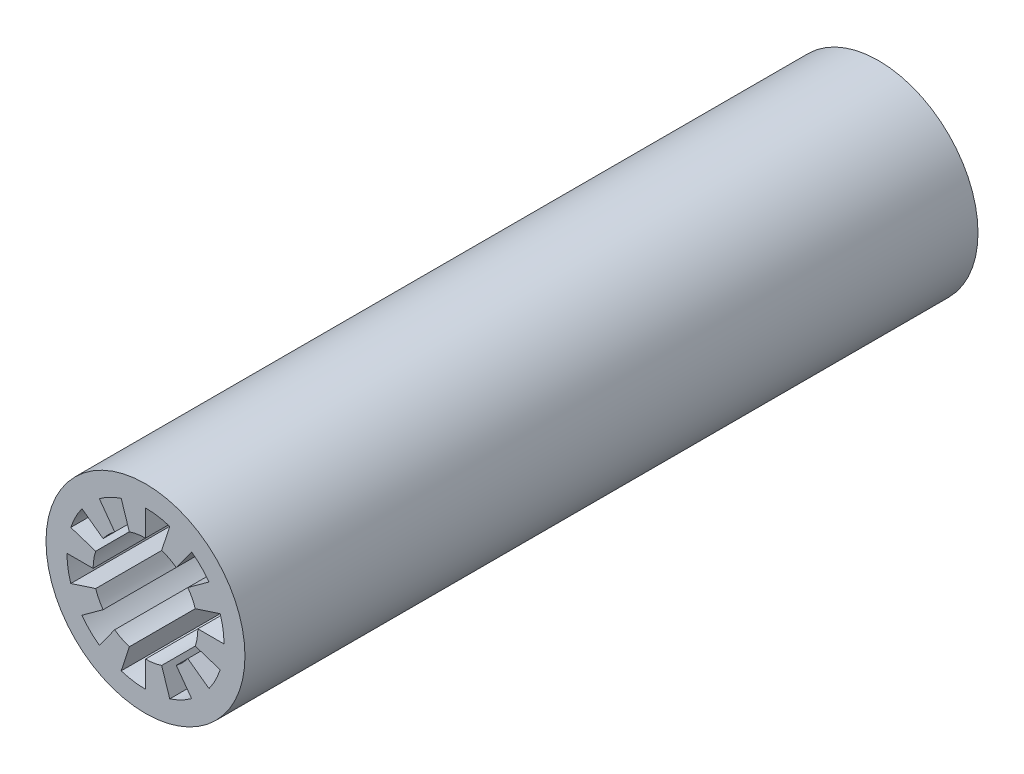
SolidWorks part; units mm, degrees
ref_plane "Front" through (0, 0, 0) normal (0, 0, 1) x (1, 0, 0)
ref_plane "Top" through (0, 0, 0) normal (0, 1, 0) x (1, 0, 0)
ref_plane "Right" through (0, 0, 0) normal (1, 0, 0) x (0, 0, -1)
sketch "Эскиз1" plane through (0, 0, 0) normal (0, 0, 1) x (1, 0, 0)
  line L0 (0, 7.5) -> (0, 5)
  line L1 (2.3176, 7.1329) -> (1.5451, 4.7553)
  line L2 (4.4084, 6.0676) -> (2.9389, 4.0451)
  line L3 (6.0676, 4.4084) -> (4.0451, 2.9389)
  line L4 (7.1329, 2.3176) -> (4.7553, 1.5451)
  line L5 (7.5, 0) -> (5, 0)
  line L6 (7.1329, -2.3176) -> (4.7553, -1.5451)
  line L7 (6.0676, -4.4084) -> (4.0451, -2.9389)
  line L8 (4.4084, -6.0676) -> (2.9389, -4.0451)
  line L9 (2.3176, -7.1329) -> (1.5451, -4.7553)
  line L10 (0, -7.5) -> (0, -5)
  line L11 (-2.3176, -7.1329) -> (-1.5451, -4.7553)
  line L12 (-4.4084, -6.0676) -> (-2.9389, -4.0451)
  line L13 (-6.0676, -4.4084) -> (-4.0451, -2.9389)
  line L14 (-7.1329, -2.3176) -> (-4.7553, -1.5451)
  line L15 (-7.5, 0) -> (-5, 0)
  line L16 (-7.1329, 2.3176) -> (-4.7553, 1.5451)
  line L17 (-6.0676, 4.4084) -> (-4.0451, 2.9389)
  line L18 (-4.4084, 6.0676) -> (-2.9389, 4.0451)
  line L19 (-2.3176, 7.1329) -> (-1.5451, 4.7553)
  arc A0 (0, 5) -> (-1.5451, 4.7553) centre (0, 0) ccw
  circle A1 centre (0, 0) radius 9.5
  arc A2 (2.9389, 4.0451) -> (1.5451, 4.7553) centre (0, 0) ccw
  arc A3 (4.7553, 1.5451) -> (4.0451, 2.9389) centre (0, 0) ccw
  arc A4 (4.7553, -1.5451) -> (5, 0) centre (0, 0) ccw
  arc A5 (2.9389, -4.0451) -> (4.0451, -2.9389) centre (0, 0) ccw
  arc A6 (0, -5) -> (1.5451, -4.7553) centre (0, 0) ccw
  arc A7 (-2.9389, -4.0451) -> (-1.5451, -4.7553) centre (0, 0) ccw
  arc A8 (-4.7553, -1.5451) -> (-4.0451, -2.9389) centre (0, 0) ccw
  arc A9 (-4.7553, 1.5451) -> (-5, 0) centre (0, 0) ccw
  arc A10 (-2.9389, 4.0451) -> (-4.0451, 2.9389) centre (0, 0) ccw
  arc A11 (-6.0676, 4.4084) -> (-7.1329, 2.3176) centre (0, 0) ccw
  arc A12 (-2.3176, 7.1329) -> (-4.4084, 6.0676) centre (0, 0) ccw
  arc A13 (2.3176, 7.1329) -> (0, 7.5) centre (0, 0) ccw
  arc A14 (6.0676, 4.4084) -> (4.4084, 6.0676) centre (0, 0) ccw
  arc A15 (7.5, 0) -> (7.1329, 2.3176) centre (0, 0) ccw
  arc A16 (6.0676, -4.4084) -> (7.1329, -2.3176) centre (0, 0) ccw
  arc A17 (2.3176, -7.1329) -> (4.4084, -6.0676) centre (0, 0) ccw
  arc A18 (-2.3176, -7.1329) -> (0, -7.5) centre (0, 0) ccw
  arc A19 (-6.0676, -4.4084) -> (-4.4084, -6.0676) centre (0, 0) ccw
  arc A20 (-7.5, 0) -> (-7.1329, -2.3176) centre (0, 0) ccw
  point P43 (0, 0)
extrude "Бобышка-Вытянуть1" add sketch "Эскиз1" along normal blind 70
